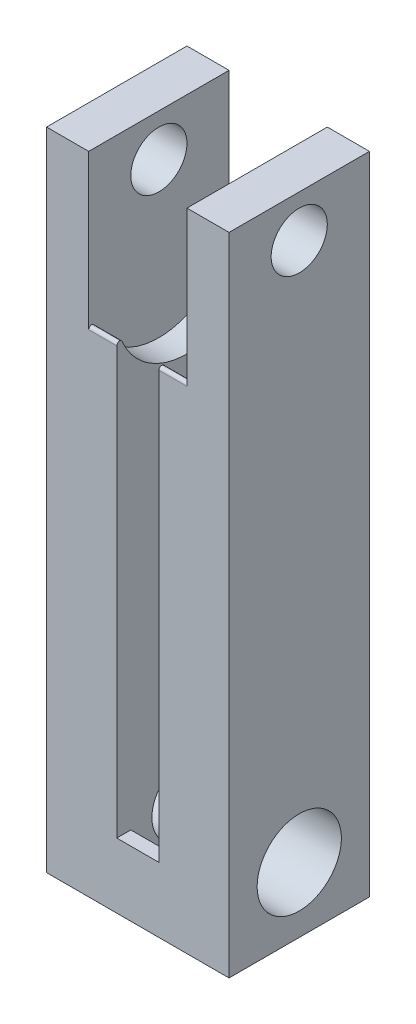
SolidWorks part; units mm, degrees
ref_plane "Front Plane" through (0, 0, 0) normal (0, 0, 1) x (1, 0, 0)
ref_plane "Top Plane" through (0, 0, 0) normal (0, 1, 0) x (1, 0, 0)
ref_plane "Right Plane" through (0, 0, 0) normal (1, 0, 0) x (0, 0, -1)
sketch "Sketch1" plane through (0, 0, 0) normal (0, 1, 0) x (1, 0, 0)
  line L1 (0, 0) -> (-65, 0)
  line L2 (0, 0) -> (0, 50)
  line L3 (0, 50) -> (-65, 50)
  line L4 (-65, 0) -> (-65, 50)
  dimension "D1" = 65
  dimension "D2" = 50
extrude "Boss-Extrude1" add sketch "Sketch1" along normal blind 10
sketch "Sketch2" plane through (0, 10, 0) normal (0, 1, 0) x (1, 0, 0)
  line L0 (-65, 0) -> (0, 0) construction
  line L1 (-65, 50) -> (-50, 50)
  line L2 (-65, 50) -> (-65, 0)
  line L3 (-65, 0) -> (-50, 0)
  line L4 (-50, 50) -> (-50, 0)
  line L6 (0, 50) -> (-15, 50)
  line L7 (0, 50) -> (0, 0)
  line L8 (0, 0) -> (-15, 0)
  line L9 (-15, 50) -> (-15, 0)
  dimension "D1" = 15
  dimension "D2" = 15
extrude "Boss-Extrude2" add sketch "Sketch2" along normal blind 70
sketch "Sketch3" plane through (-50, 0, 0) normal (1, 0, 0) x (0, 0, -1)
  line L0 (0, 10) -> (50, 10) construction
  line L1 (50, 80) -> (50, 0) construction
  circle A0 centre (25, 65) radius 10
  dimension "D1" = 20
  dimension "D2" = 55
  dimension "D3" = 25
extrude "Cut-Extrude1" cut sketch "Sketch3" against normal through all both and the other way through all
sketch "Sketch5" plane through (-50, 0, 0) normal (1, 0, 0) x (0, 0, -1)
  line L0 (50, 80) -> (50, 10) construction
  line L1 (0, 80) -> (0, 10) construction
  line L3 (0, 10) -> (50, 10) construction
  line L8 (50, 35) -> (0, 35)
  arc A0 (50, 35) -> (0, 35) centre (25, 35) cw
  line M2 (0, 10) -> (50, 10)
  line M3 (50, 10) -> (50, 80)
  line M5 (0, 80) -> (0, 10)
extrude "Boss-Extrude7" add sketch "Sketch5" along normal up to next contours A0 M3 M2 | A0 M2 M5
fillet "Fillet1" radius 1 2 edges at (-32.5, 35, -50) (-32.5, 35, 0)
sketch "Sketch6" plane through (0, 0, 0) normal (0, -1, 0) x (1, 0, 0)
  line L0 (0, -50) -> (-65, -50) construction
  line L1 (-65, 0) -> (-40, 0)
  line L2 (-65, 0) -> (-65, -50)
  line L3 (-65, -50) -> (-40, -50)
  line L4 (-40, 0) -> (-40, -50)
  dimension "D1" = 25
extrude "Boss-Extrude8" add sketch "Sketch6" along normal blind 150
sketch "Sketch7" plane through (-40, 0, 0) normal (1, 0, 0) x (0, 0, -1)
  line L0 (50, -150) -> (0, -150) construction
  circle A0 centre (25, -126.8255) radius 12.5
  point P2 (0, 0)
  point P5 (25, -150)
  dimension "D1" = 25
extrude "Cut-Extrude2" cut sketch "Sketch7" against normal blind 150
sketch "Sketch8" plane through (0, 0, 0) normal (0, -1, 0) x (1, 0, 0)
  line L0 (0, -50) -> (-40, -50) construction
  line L1 (-25, -50) -> (-40, -50)
  line L2 (-25, -50) -> (-25, 0)
  line L3 (-25, 0) -> (-40, 0)
  line L4 (-40, -50) -> (-40, 0)
  line L5 (-40, 0) -> (0, 0) construction
  line L9 (-40, -50) -> (-40, 0) construction
  dimension "D2" = 15
extrude "Cut-Extrude3" cut sketch "Sketch8" against normal blind 150
sketch "Sketch11" plane through (0, 0, 0) normal (0, -1, 0) x (1, 0, 0)
  line L1 (0, -50) -> (-25, -50)
  line L2 (0, -50) -> (0, 0)
  line L3 (0, 0) -> (-25, 0)
  line L4 (-25, -50) -> (-25, 0)
extrude "Boss-Extrude9" add sketch "Sketch11" along normal blind 150
sketch "Sketch12" plane through (-25, 0, 0) normal (-1, 0, 0) x (0, 0, 1)
  circle A0 centre (-25, -126.8255) radius 15
  circle A3 centre (-25, -126.8255) radius 12.5 construction
  dimension "D1" = 30
extrude "Cut-Extrude4" cut sketch "Sketch12" against normal blind 150
sketch "Sketch14" plane through (-25, 0, 0) normal (-1, 0, 0) x (0, 0, 1)
  line L1 (-50, 25) -> (-50, -150) construction
  line L2 (-5, -126.8255) -> (0, -126.8255)
  line L3 (-45, -126.8255) -> (-50, -126.8255)
  line L4 (0, -126.8255) -> (0, -150)
  line L5 (0, -150) -> (-50, -150)
  line L6 (-50, -150) -> (-50, -126.8255)
  line L7 (0, 25) -> (0, -150) construction
  arc A1 (-45, -126.8255) -> (-5, -126.8255) centre (-25, -126.8255) ccw
  point P7 (0, 0)
  point P8 (0, 0)
  point P9 (0, 0)
  dimension "D1" = 5
  dimension "D2" = 5
extrude "Boss-Extrude10" add sketch "Sketch14" along normal up to surface (15 mm away) up to face at (-40, -126.8255, -37.5)
